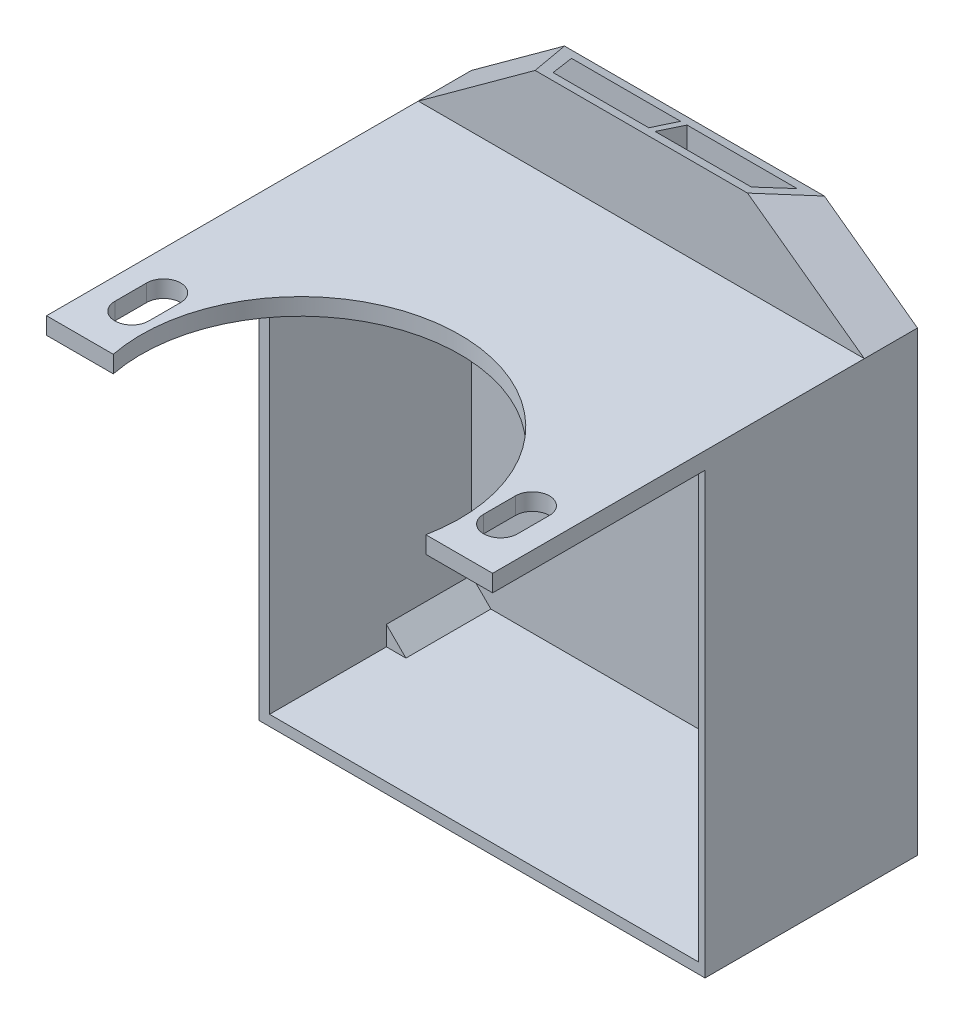
SolidWorks part; units mm, degrees
ref_plane "前视基准面" through (0, 0, 0) normal (0, 0, 1) x (1, 0, 0)
ref_plane "上视基准面" through (0, 0, 0) normal (0, 1, 0) x (1, 0, 0)
ref_plane "右视基准面" through (0, 0, 0) normal (1, 0, 0) x (0, 0, -1)
sketch "草图1" plane through (0, 0, 0) normal (0, 0, 1) x (1, 0, 0)
  line L1 (0, 0) -> (42, 0)
  line L2 (0, 0) -> (0, 43)
  line L3 (0, 43) -> (42, 43)
  line L4 (42, 0) -> (42, 43)
  dimension "D1" = 42
  dimension "D2" = 43
extrude "凸台-拉伸1" add sketch "草图1" along normal blind 20
sketch "草图2" plane through (0, 0, 20) normal (0, 0, 1) x (1, 0, 0)
  line L0 (0, 43) -> (0, 0) construction
  line L1 (1, 41.4) -> (41.4, 41.4)
  line L2 (1, 41.4) -> (1, 1)
  line L3 (1, 1) -> (41.4, 1)
  line L4 (41.4, 41.4) -> (41.4, 1)
  line L5 (0, 0) -> (42, 0) construction
  dimension "D1" = 40.4
  dimension "D2" = 40.4
  dimension "D3" = 1
  dimension "D4" = 1
extrude "切除-拉伸1" cut sketch "草图2" against normal blind 19
sketch "草图3" plane through (0, 0, 0) normal (0, 0, -1) x (-1, 0, 0)
  line L0 (-42, 43) -> (0, 43)
  line L1 (0, 43) -> (-11, 51)
  line L2 (-11, 51) -> (-31, 51)
  line L3 (-31, 51) -> (-42, 43)
  line L4 (-21, 43) -> (-21, 56.679) construction
  dimension "D1" = 20
  dimension "D2" = 8
extrude "凸台-拉伸2" add sketch "草图3" against normal blind 5
sketch "草图5" plane through (0, 0, 1) normal (0, 0, 1) x (1, 0, 0)
  line L0 (1, 41.4) -> (1, 42.4345)
  line L1 (1, 42.4345) -> (13.1565, 51.8028)
  line L2 (13.1565, 51.8028) -> (28.8496, 51.8028)
  line L3 (28.8496, 51.8028) -> (41.4, 42.4345)
  line L4 (41.4, 42.4345) -> (41.4, 41.4)
  line L5 (41.4, 41.4) -> (1, 41.4) construction
  line L6 (41.4, 41.4) -> (1, 41.4) construction
  line L7 (41.4, 41.4) -> (1, 41.4)
extrude "切除-拉伸2" cut sketch "草图5" along normal blind 3
sketch "草图6" plane through (0, 0, 1) normal (0, 0, 1) x (1, 0, 0)
  line L0 (1, 41.4) -> (1, 39.9541)
  line L1 (1, 41.4) -> (1, 1) construction
  line L2 (1, 39.9541) -> (2.3449, 41.4)
  line L3 (41.4, 41.4) -> (1, 41.4) construction
  line L4 (2.3449, 41.4) -> (1, 41.4)
  line L5 (41.4, 41.4) -> (41.4, 39.9541)
  line L6 (41.4, 1) -> (41.4, 42.4345) construction
  line L7 (41.4, 39.9541) -> (39.9541, 41.4)
  line L8 (39.9541, 41.4) -> (41.4, 41.4)
  line L9 (41.4, 1) -> (41.4, 2.8369)
  line L10 (41.4, 2.8369) -> (39.5631, 1)
  line L11 (1, 1) -> (41.4, 1) construction
  line L12 (39.5631, 1) -> (41.4, 1)
  line L13 (1, 1) -> (1, 2.8369)
  line L14 (1, 2.8369) -> (2.8369, 1)
  line L15 (2.8369, 1) -> (1, 1)
extrude "凸台-拉伸3" add sketch "草图6" along normal blind 8
sketch "草图7" plane through (0, 0, 20) normal (0, 0, 1) x (1, 0, 0)
  line L0 (42, 0) -> (42, 43) construction
  line L1 (0, 43) -> (42, 43)
  line L2 (0, 43) -> (0, 41.4)
  line L3 (0, 41.4) -> (42, 41.4)
  line L4 (42, 43) -> (42, 41.4)
extrude "凸台-拉伸4" add sketch "草图7" along normal blind 20
sketch "草图8" plane through (0, 41.4, 0) normal (0, -1, 0) x (1, 0, 0)
  line L0 (21, 40) -> (21, 24.4906) construction
  line L1 (0, 40) -> (42, 40) construction
  line L2 (3.64, 32.61) -> (3.64, 35.61) construction
  line L3 (2.04, 32.61) -> (2.04, 35.61)
  line L4 (5.24, 32.61) -> (5.24, 35.61)
  line L5 (38.36, 32.61) -> (38.36, 35.61) construction
  line L6 (39.96, 32.61) -> (39.96, 35.61)
  line L7 (36.76, 32.61) -> (36.76, 35.61)
  line L8 (0, 20) -> (42, 20) construction
  arc A0 (2.04, 32.61) -> (5.24, 32.61) centre (3.64, 32.61) ccw
  arc A1 (5.24, 35.61) -> (2.04, 35.61) centre (3.64, 35.61) ccw
  arc A2 (39.96, 32.61) -> (36.76, 32.61) centre (38.36, 32.61) cw
  arc A3 (36.76, 35.61) -> (39.96, 35.61) centre (38.36, 35.61) cw
  circle A4 centre (21, 37.0884) radius 15
  point P6 (3.64, 34.11)
  point P13 (38.36, 34.11)
  dimension "D5" = 30
  dimension "D1" = 3.2
  dimension "D2" = 3
  dimension "D3" = 34.72
  dimension "D4" = 14.11
  dimension "D6" = 17.0884
extrude "切除-拉伸3" cut sketch "草图8" against normal blind 20
sketch "草图9" plane through (0, 0, 1) normal (0, 0, 1) x (1, 0, 0)
  line L0 (11, 51) -> (31, 51) construction
  line L1 (20.7, 51) -> (21.3, 51)
  line L2 (20.7, 51) -> (20.7, 41.4)
  line L3 (20.7, 41.4) -> (21.3, 41.4)
  line L4 (21.3, 51) -> (21.3, 41.4)
  line L5 (6, 41.4) -> (36, 41.4) construction
  line L6 (21, 51) -> (21, 38.3971) construction
  dimension "D1" = 0.6
extrude "凸台-拉伸5" add sketch "草图9" along direction (0, 0, -1) on the side of the normal up to next (3 mm away)
sketch "草图10" plane through (20.7, 0, 0) normal (-1, 0, 0) x (0, 0, 1)
  line L0 (5, 51) -> (-3.0342, 48.3895)
  line L1 (-3.0342, 48.3895) -> (-3.0342, 51)
  line L2 (-3.0342, 51) -> (5, 51)
  dimension "D1" = 18
extrude "切除-拉伸4" cut sketch "草图10" against normal blind 20 and the other way blind 20
